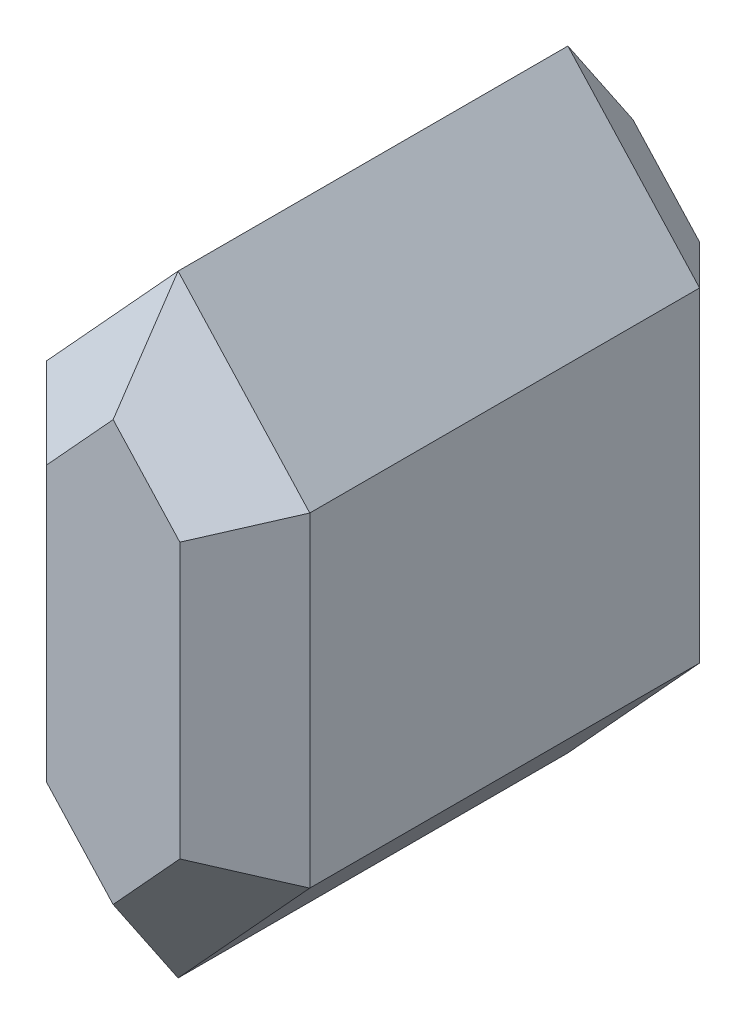
SolidWorks part; units mm, degrees
ref_plane "Front Plane" through (0, 0, 0) normal (0, 0, 1) x (1, 0, 0)
ref_plane "Top Plane" through (0, 0, 0) normal (0, 1, 0) x (1, 0, 0)
ref_plane "Right Plane" through (0, 0, 0) normal (1, 0, 0) x (0, 0, -1)
sketch "Sketch1" plane through (0, 0, 0) normal (0, 0, 1) x (1, 0, 0)
  line L1 (0, 18.8473) -> (-4.0535, 14.4237)
  line L2 (-4.0535, 14.4237) -> (-4.0535, 4.4237)
  line L3 (-4.0535, 4.4237) -> (0, 0)
  line L4 (0, 0) -> (4.0535, 4.4237)
  line L5 (4.0535, 4.4237) -> (4.0535, 14.4237)
  line L7 (0, 18.8473) -> (4.0535, 14.4237)
  point P6 (0, 0)
  dimension "D1" = 6
  dimension "D2" = 10
  dimension "D3" = 6
  dimension "D4" = 85
  dimension "D5" = 10
  dimension "D6" = 85
extrude "Boss-Extrude1" add sketch "Sketch1" along normal blind 16
chamfer "Chamfer1" distance 2 angle 45 12 edges at (-2.0268, 2.2118, 16) (-4.0535, 9.4237, 16) (-2.0268, 16.6355, 16) (2.0268, 16.6355, 16) (4.0535, 9.4237, 16) (2.0268, 2.2118, 16) (4.0535, 9.4237, 0) (2.0268, 16.6355, 0) (-2.0268, 16.6355, 0) (-4.0535, 9.4237, 0) (-2.0268, 2.2118, 0) (2.0268, 2.2118, 0)
scale "Scale2" scale about origin uniform scaling yes scale factor 0.95
